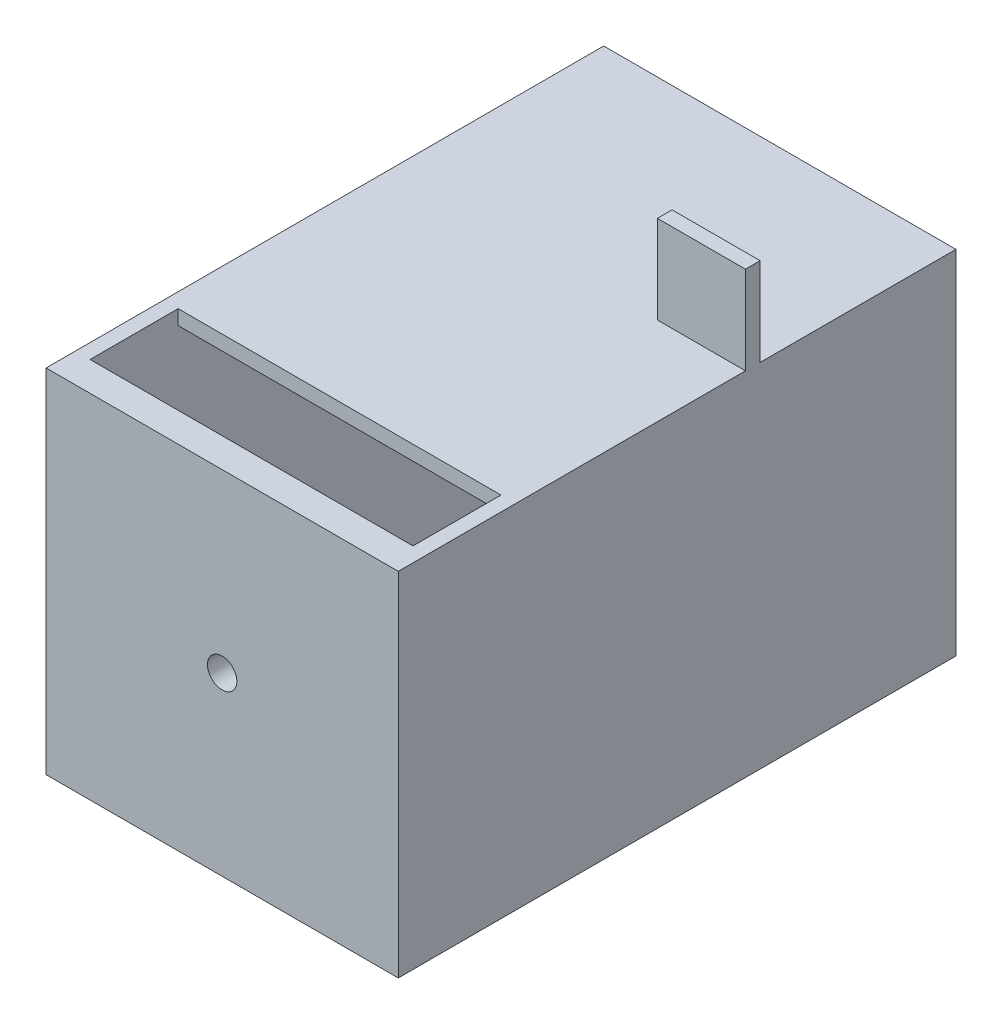
SolidWorks part; units mm, degrees
ref_plane "Front Plane" through (0, 0, 0) normal (0, 0, 1) x (1, 0, 0)
ref_plane "Top Plane" through (0, 0, 0) normal (0, 1, 0) x (1, 0, 0)
ref_plane "Right Plane" through (0, 0, 0) normal (1, 0, 0) x (0, 0, -1)
sketch "Sketch1" plane through (0, 0, 0) normal (0, 0, 1) x (1, 0, 0)
  line L1 (-60, 60) -> (60, 60)
  line L2 (-60, 60) -> (-60, -60)
  line L3 (-60, -60) -> (-40, -60)
  line L4 (60, 60) -> (60, -60)
  line L5 (-60, 60) -> (60, -60) construction
  line L6 (-60, -60) -> (60, 60) construction
  line L7 (55, -55) -> (40, -55)
  line L8 (55, -55) -> (55, 55)
  line L9 (55, 55) -> (-55, 55)
  line L10 (-55, -55) -> (-55, 55)
  line L11 (55, -55) -> (-55, 55) construction
  line L12 (55, 55) -> (-55, -55) construction
  line L13 (40, -60) -> (60, -60)
  line L15 (-40, -55) -> (-55, -55)
  line L16 (0, 0) -> (0, 115.2788) construction
  line L17 (0, 0) -> (-99.6829, 0) construction
  line L19 (-40, -60) -> (-40, -55)
  line L20 (40, -60) -> (40, -55)
  point P0 (0, 0)
  point P6 (0, 0)
  point P13 (-40, -57.5)
  dimension "D1" = 120
  dimension "D2" = 110
  dimension "D5" = 20
extrude "Boss-Extrude1" add sketch "Sketch1" along normal blind 180
sketch "Sketch2" plane through (0, 0, 180) normal (0, 0, 1) x (1, 0, 0)
  line L1 (-60, 60) -> (60, 60)
  line L2 (-60, 60) -> (-60, -60)
  line L3 (-60, -60) -> (60, -60)
  line L4 (60, 60) -> (60, -60)
  line L5 (-60, 60) -> (60, -60) construction
  line L6 (-60, -60) -> (60, 60) construction
  point P0 (0, 0)
extrude "Boss-Extrude2" add sketch "Sketch2" along normal blind 10
sketch "Sketch3" plane through (0, 0, 190) normal (0, 0, 1) x (1, 0, 0)
  circle A0 centre (0, 0) radius 5
  dimension "D1" = 10
extrude "Cut-Extrude1" cut sketch "Sketch3" against normal blind 10
sketch "Sketch4" plane through (0, 60, 0) normal (0, 1, 0) x (1, 0, 0)
  line L0 (60, -190) -> (60, -180) construction
  line L1 (60, -190) -> (60, 0) construction
  line L2 (60, -180) -> (55, -180) construction
  line L3 (-60, -190) -> (-60, 0) construction
  line L4 (55, -180) -> (-55, -180)
  line L5 (55, -180) -> (55, -150)
  line L6 (55, -150) -> (-55, -150)
  line L7 (-55, -180) -> (-55, -150)
  point P11 (0, 0)
  dimension "D1" = 10
  dimension "D2" = 5
  dimension "D3" = 5
  dimension "D4" = 30
extrude "Cut-Extrude2" cut sketch "Sketch4" against normal blind 10
sketch "Sketch5" plane through (0, 60, 0) normal (0, 1, 0) x (1, 0, 0)
  line L0 (60, 0) -> (60, -66.7018) construction
  line L1 (60, -190) -> (60, 0) construction
  line L3 (60, -66.7018) -> (30, -66.7018)
  line L4 (60, -66.7018) -> (60, -71.7018)
  line L5 (60, -71.7018) -> (30, -71.7018)
  line L6 (30, -66.7018) -> (30, -71.7018)
  point P8 (60, -69.2018)
  dimension "D1" = 30
  dimension "D2" = 5
extrude "Boss-Extrude3" add sketch "Sketch5" along normal blind 30
